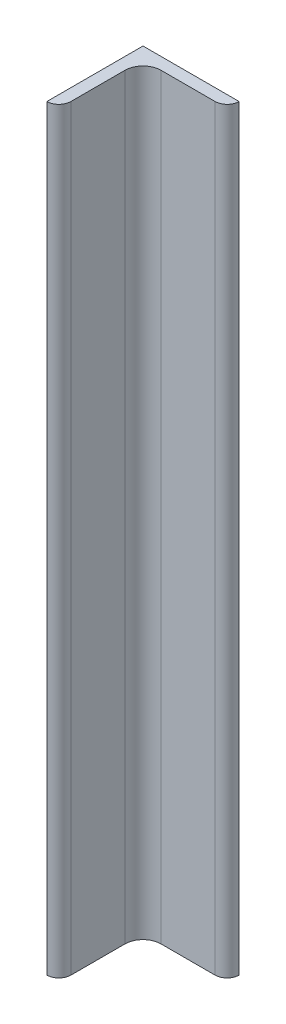
SolidWorks part; units mm, degrees
ref_plane "Alzado" through (0, 0, 0) normal (0, 0, 1) x (1, 0, 0)
ref_plane "Planta" through (0, 0, 0) normal (0, 1, 0) x (1, 0, 0)
ref_plane "Vista lateral" through (0, 0, 0) normal (1, 0, 0) x (0, 0, -1)
sketch "Croquis1" plane through (0, 0, 0) normal (1, 0, 0) x (0, 0, -1)
  line L0 (0, 0) -> (0, 200)
  dimension "D1" = 200
other "Hierro angular 1 X 1 X 0.125(1)"
ref_plane "Plano1" through (0, 0, 0) normal (0, 1, 0) x (0, 0, 1)
sketch "Sketch1" plane through (0, 0, 0) normal (0, 1, 0) x (0, 0, 1)
  line L0 (0, 0) -> (0, 25.4)
  line L1 (0, 25.4) -> (0.0051, 25.4)
  line L2 (3.175, 22.2301) -> (3.175, 7.9375)
  line L3 (7.9375, 3.175) -> (22.2301, 3.175)
  line L4 (25.4, 0.0051) -> (25.4, 0)
  line L5 (25.4, 0) -> (0, 0)
  arc A0 (25.4, 0.0051) -> (22.2301, 3.175) centre (22.2301, 0.0051) ccw
  arc A1 (0.0051, 25.4) -> (3.175, 22.2301) centre (0.0051, 22.2301) cw
  arc A2 (7.9375, 3.175) -> (3.175, 7.9375) centre (7.9375, 7.9375) cw
  point P10 (12.7, 0)
  point P14 (0, 12.7)
  point P15 (3.175, 12.7)
  point P16 (12.7, 3.175)
  point P17 (3.175, 25.4)
  point P18 (25.4, 3.175)
  point P19 (0, 0)
  dimension "D2" = 0.0051
  dimension "Radius_1" = 4.7625
  dimension "D1" = 3.175
  dimension "H_leg" = 25.4
equation "\"D1@Croquis1\"=200"
